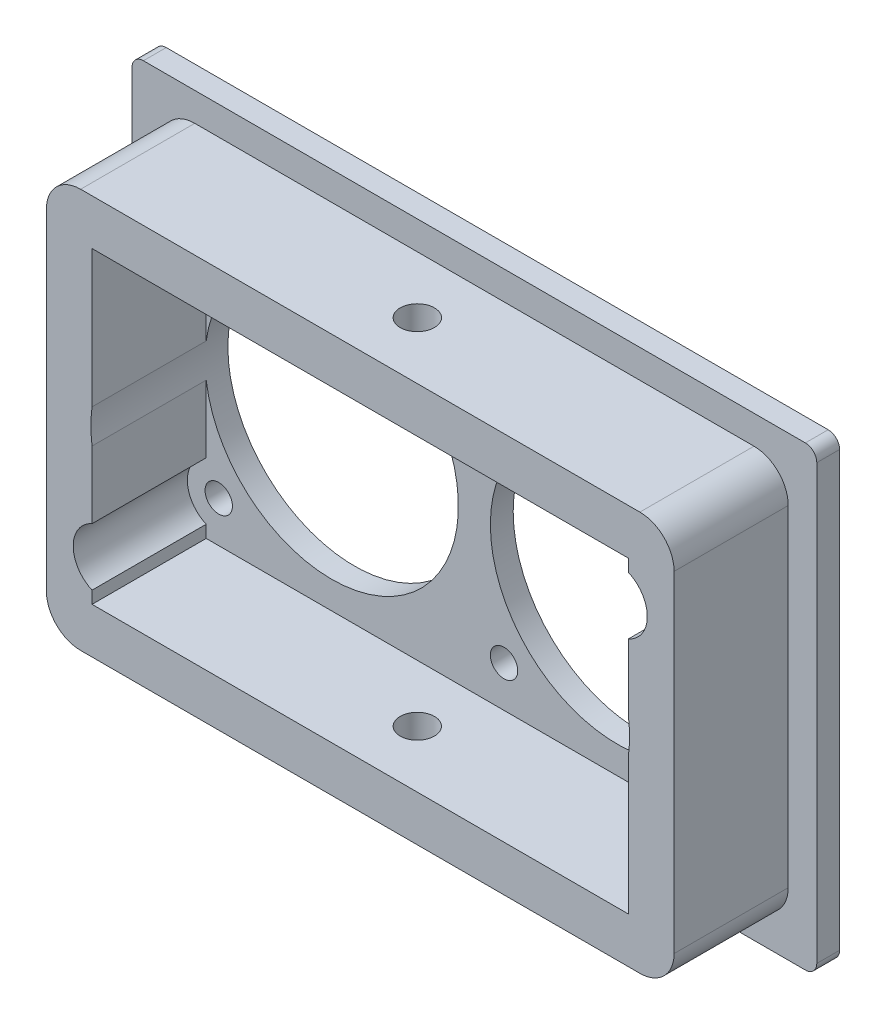
SolidWorks part; units mm, degrees
ref_plane "Plan de face" through (0, 0, 0) normal (0, 0, 1) x (1, 0, 0)
ref_plane "Plan de dessus" through (0, 0, 0) normal (0, 1, 0) x (1, 0, 0)
ref_plane "Plan de droite" through (0, 0, 0) normal (1, 0, 0) x (0, 0, -1)
sketch "Esquisse1" plane through (0, 0, 0) normal (0, 0, 1) x (1, 0, 0)
  line L1 (0, 0) -> (60, 0)
  line L2 (0, 0) -> (0, 40)
  line L3 (0, 40) -> (60, 40)
  line L4 (60, 0) -> (60, 40)
  dimension "D1" = 60
  dimension "D2" = 40
extrude "Boss.-Extru.1" add sketch "Esquisse1" along normal blind 2
sketch "Esquisse2" plane through (0, 0, 2) normal (0, 0, 1) x (1, 0, 0)
  line L12 (2.5, 37.5) -> (2.5, 2.5)
  line L13 (2.5, 2.5) -> (57.5, 2.5)
  line L14 (57.5, 2.5) -> (57.5, 37.5)
  line L15 (57.5, 37.5) -> (2.5, 37.5)
  line L16 (2.5, 37.5) -> (2.5, 2.5)
  line L17 (2.5, 2.5) -> (57.5, 2.5)
  line L18 (57.5, 2.5) -> (57.5, 37.5)
  line L19 (57.5, 37.5) -> (2.5, 37.5)
  dimension "D1" = 2.5
extrude "Boss.-Extru.2" add sketch "Esquisse2" along normal blind 10
fillet "Congé1" radius 3 4 edges at (2.5, 37.5, 7) (2.5, 2.5, 7) (57.5, 2.5, 7) (57.5, 37.5, 7)
fillet "Congé2" radius 1 4 edges at (0, 0, 1) (60, 0, 1) (60, 40, 1) (0, 40, 1)
sketch "Esquisse3" plane through (0, 0, 12) normal (0, 0, 1) x (1, 0, 0)
  line L12 (53.5, 33.5) -> (6.5, 33.5)
  line L13 (6.5, 33.5) -> (6.5, 6.5)
  line L14 (6.5, 6.5) -> (53.5, 6.5)
  line L15 (53.5, 6.5) -> (53.5, 33.5)
  line L16 (53.5, 33.5) -> (6.5, 33.5)
  line L17 (6.5, 33.5) -> (6.5, 6.5)
  line L18 (6.5, 6.5) -> (53.5, 6.5)
  line L19 (53.5, 6.5) -> (53.5, 33.5)
  dimension "D1" = 4
extrude "Enlèv. mat.-Extru.1" cut sketch "Esquisse3" against normal up to surface (10 mm away) up to face at (30, 20, 2)
sketch "Esquisse4" plane through (0, 37.5, 0) normal (0, 1, 0) x (1, 0, 0)
  line L0 (30, -2) -> (30, -7) construction
  line L1 (59, -2) -> (1, -2) construction
  circle A0 centre (30, -7) radius 1.5
  dimension "D1" = 3
  dimension "D2" = 5
extrude "Enlèv. mat.-Extru.2" cut sketch "Esquisse4" against normal through all
sketch "Esquisse5" plane through (0, 0, 0) normal (0, 0, -1) x (-1, 0, 0)
  line L0 (-60, 20) -> (-42.5, 20) construction
  line L1 (-60, 1) -> (-60, 39) construction
  line L2 (-42.5, 20) -> (-17.5, 20) construction
  line L3 (-17.5, 20) -> (0, 20) construction
  line L4 (0, 39) -> (0, 1) construction
  line L5 (-52.4, 29.9) -> (-32.6, 10.1) construction
  line L6 (-27.4, 29.9) -> (-7.6, 10.1) construction
  circle A0 centre (-42.5, 20) radius 11.1
  circle A1 centre (-17.5, 20) radius 11.1
  circle A2 centre (-52.4, 29.9) radius 1.2
  circle A3 centre (-32.6, 10.1) radius 1.2
  circle A4 centre (-27.4, 29.9) radius 1.2
  circle A5 centre (-7.6, 10.1) radius 1.2
  point P18 (0, 0)
  point P19 (0, 0)
  dimension "D1" = 22.2
  dimension "D5" = 2.4
  dimension "D2" = 25
  dimension "D3" = 19.8
  dimension "D4" = 45
extrude "Enlèv. mat.-Extru.3" cut sketch "Esquisse5" against normal through all
sketch "Esquisse6" plane through (0, 0, 2) normal (0, 0, 1) x (1, 0, 0)
  circle A0 centre (7.6, 10.1) radius 2.75
  circle A1 centre (52.4, 29.9) radius 2.75
  dimension "D1" = 5.5
extrude "Enlèv. mat.-Extru.4" cut sketch "Esquisse6" along normal through all
